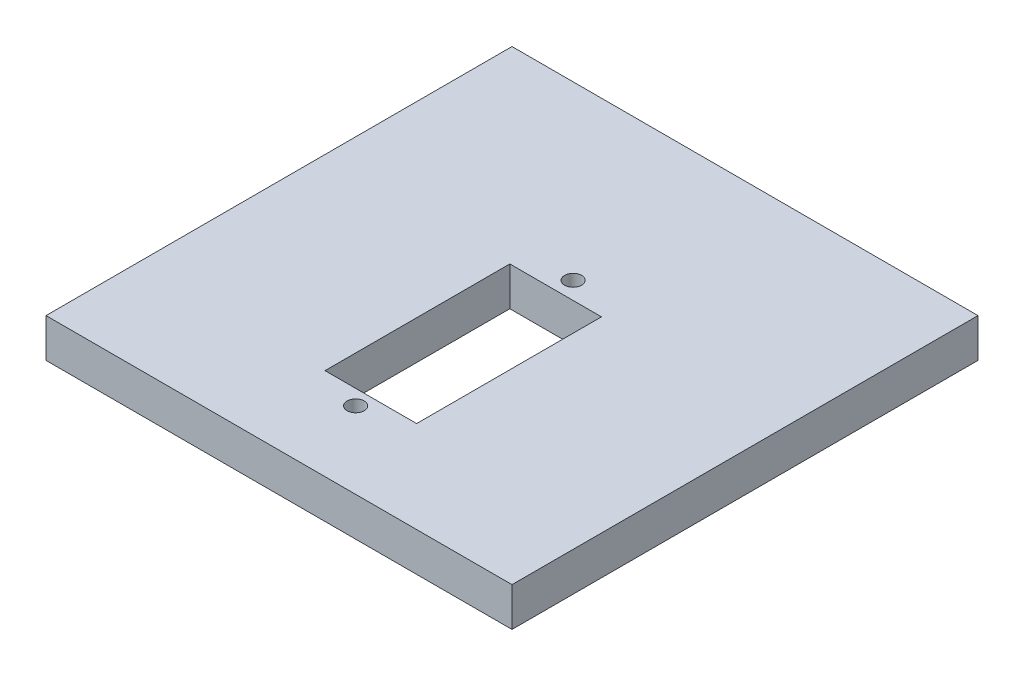
SolidWorks part; units mm, degrees
ref_plane "前视基准面" through (0, 0, 0) normal (0, 0, 1) x (1, 0, 0)
ref_plane "上视基准面" through (0, 0, 0) normal (0, 1, 0) x (1, 0, 0)
ref_plane "右视基准面" through (0, 0, 0) normal (1, 0, 0) x (0, 0, -1)
other "Configuration Table"
sketch "草图1" plane through (0, 0, 0) normal (0, 1, 0) x (1, 0, 0)
  line L0 (30, 0) -> (30, -60) construction
  line L1 (0, 0) -> (60, 0)
  line L2 (0, 0) -> (0, -60)
  line L3 (0, -60) -> (60, -60)
  line L4 (60, 0) -> (60, -60)
  line L6 (24.1, -24.38) -> (35.9, -24.38)
  line L7 (24.1, -24.38) -> (24.1, -48.18)
  line L8 (24.1, -48.18) -> (35.9, -48.18)
  line L9 (35.9, -24.38) -> (35.9, -48.18)
  line L10 (24.1, -20.08) -> (35.9, -20.08)
  line L11 (24.1, -20.08) -> (24.1, -52.18)
  line L12 (24.1, -52.18) -> (35.9, -52.18)
  line L13 (35.9, -20.08) -> (35.9, -52.18)
  circle A0 centre (30, -30) radius 2.4
  circle A1 centre (30, -22.13) radius 1.1
  circle A2 centre (30, -50.13) radius 1.1
  point P7 (30, -30)
  point P8 (-23.8744, -27.9404)
  dimension "D3" = 23.8
  dimension "D9" = 2.2
  dimension "D11" = 2.2
  dimension "D1" = 60
  dimension "D2" = 60
  dimension "D4" = 11.8
  dimension "D5" = 5.62
  dimension "D6" = 5.9
  dimension "D7" = 32.1
  dimension "D8" = 4.3
  dimension "D10" = 2.05
  dimension "D12" = 2.05
extrude "凸台-拉伸1" add sketch "草图1" along normal blind 5 contours L0 L1 L2 L3 L12 L11 L7 L10 | L1 L0 L10 L13 L9 L12 L3 L4 | L0 L8 L11 L12 A2 | L8 L0 A2 L12 L13 | L0 L10 L11 L6 A1 | L10 L0 A1 L6 L13
